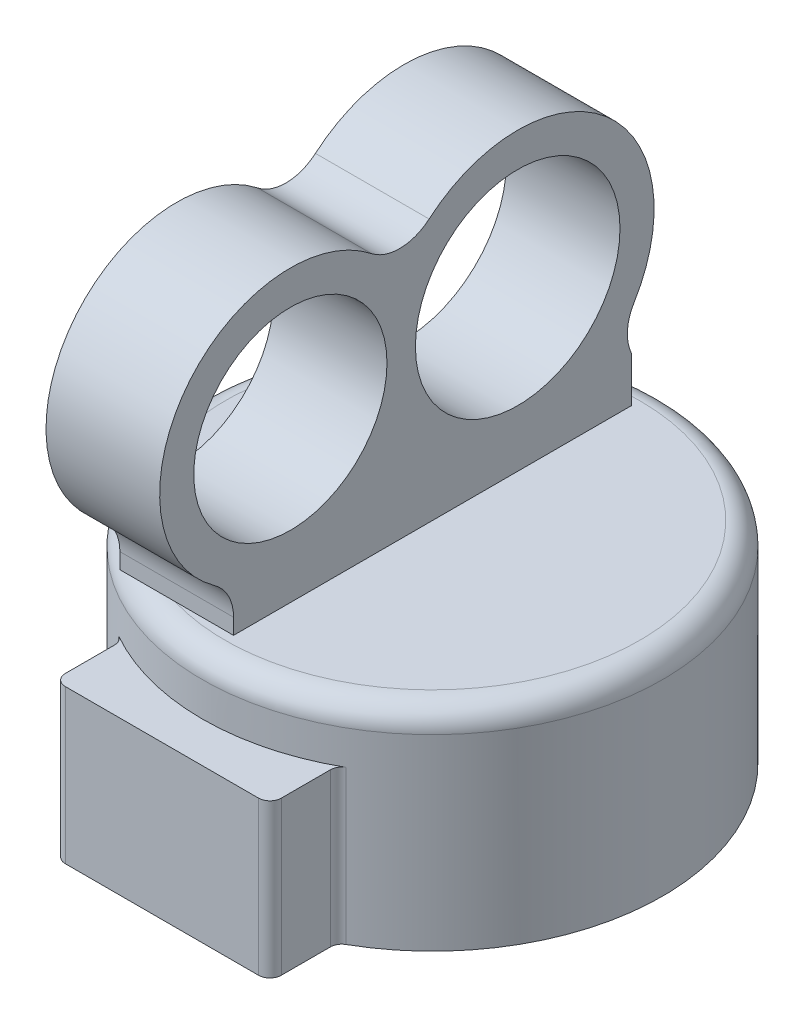
SolidWorks part; units mm, degrees
ref_plane "Front Plane" through (0, 0, 0) normal (0, 0, 1) x (1, 0, 0)
ref_plane "Top Plane" through (0, 0, 0) normal (0, 1, 0) x (1, 0, 0)
ref_plane "Right Plane" through (0, 0, 0) normal (1, 0, 0) x (0, 0, -1)
sketch "Sketch1" plane through (0, 0, 0) normal (0, 1, 0) x (1, 0, 0)
  line L0 (-9.5, -18.4746) -> (-9.5, -22.8) construction
  line L1 (8.5, -23.8) -> (-8.5, -23.8) construction
  line L2 (9.5, -22.8) -> (9.5, -18.4746) construction
  line L3 (-9.5, -18.4746) -> (-9.5, -22.8)
  line L4 (8.5, -23.8) -> (-8.5, -23.8)
  line L5 (9.5, -22.8) -> (9.5, -18.4746)
  arc A0 (10.0059, -17.6052) -> (-10.0059, -17.6052) centre (0, 0) ccw
  circle A1 centre (0, 0) radius 20.25 construction
  arc A2 (-9.5, -18.4746) -> (-10.0059, -17.6052) centre (-10.5, -18.4746) ccw construction
  arc A3 (10.0059, -17.6052) -> (9.5, -18.4746) centre (10.5, -18.4746) ccw construction
  arc A4 (-9.5, -22.8) -> (-8.5, -23.8) centre (-8.5, -22.8) ccw construction
  arc A5 (8.5, -23.8) -> (9.5, -22.8) centre (8.5, -22.8) ccw construction
  arc A6 (-9.5, -18.4746) -> (-10.0059, -17.6052) centre (-10.5, -18.4746) ccw
  arc A7 (10.0059, -17.6052) -> (9.5, -18.4746) centre (10.5, -18.4746) ccw
  arc A8 (-9.5, -22.8) -> (-8.5, -23.8) centre (-8.5, -22.8) ccw
  arc A9 (8.5, -23.8) -> (9.5, -22.8) centre (8.5, -22.8) ccw
  arc A10 (-10.0059, -17.6052) -> (10.0059, -17.6052) centre (0, 0) ccw construction
extrude "Boss-Extrude1" add sketch "Sketch1" along normal up to surface (13.5 mm away)
sketch "Sketch2" plane through (0, 13.5, 0) normal (0, 1, 0) x (1, 0, 0)
  circle A0 centre (0, 0) radius 20.25
extrude "Boss-Extrude2" add sketch "Sketch2" along normal up to surface (5 mm away)
fillet "Fillet1" radius 2 1 edges at (0, 18.5, -20.25)
sketch "Sketch3" plane through (0, 0, 0) normal (1, 0, 0) x (0, 0, -1)
  line L3 (17.5, 18.5) -> (17.5, 22.5)
  line L4 (-17.5, 19.8806) -> (-17.5, 18.5)
  line L5 (-17.5, 18.5) -> (17.5, 18.5)
  line L6 (17.5, 18.5) -> (17.5, 22.5)
  line L7 (-17.5, 19.8806) -> (-17.5, 18.5)
  line L8 (-17.5, 18.5) -> (17.5, 18.5)
  circle A0 centre (7.5, 32.5) radius 9 construction
  circle A1 centre (-12.5, 32.5) radius 8.5 construction
  circle A2 centre (7.5, 32.5) radius 9
  circle A3 centre (-12.5, 32.5) radius 8.5
  arc A5 (17.7343, 26.2343) -> (17.5, 22.5) centre (21.1458, 24.1458) ccw
  arc A6 (17.7343, 26.2343) -> (-0.2953, 41.6232) centre (7.5, 32.5) ccw
  arc A7 (-5.3728, 41.5251) -> (-0.2953, 41.6232) centre (-2.8938, 44.6643) ccw
  arc A8 (-5.3728, 41.5251) -> (-19.1774, 23.1372) centre (-12.5, 32.5) ccw
  arc A9 (-17.5, 19.8806) -> (-19.1774, 23.1372) centre (-21.5, 19.8806) ccw
  arc A10 (17.7343, 26.2343) -> (17.5, 22.5) centre (21.1458, 24.1458) ccw
  arc A11 (17.7343, 26.2343) -> (-0.2953, 41.6232) centre (7.5, 32.5) ccw
  arc A12 (-5.3728, 41.5251) -> (-0.2953, 41.6232) centre (-2.8938, 44.6643) ccw
  arc A13 (-5.3728, 41.5251) -> (-19.1774, 23.1372) centre (-12.5, 32.5) ccw
  arc A14 (-17.5, 19.8806) -> (-19.1774, 23.1372) centre (-21.5, 19.8806) ccw
  dimension "D1" = 0
extrude "Boss-Extrude3" add sketch "Sketch3" against normal up to surface (10 mm away)
